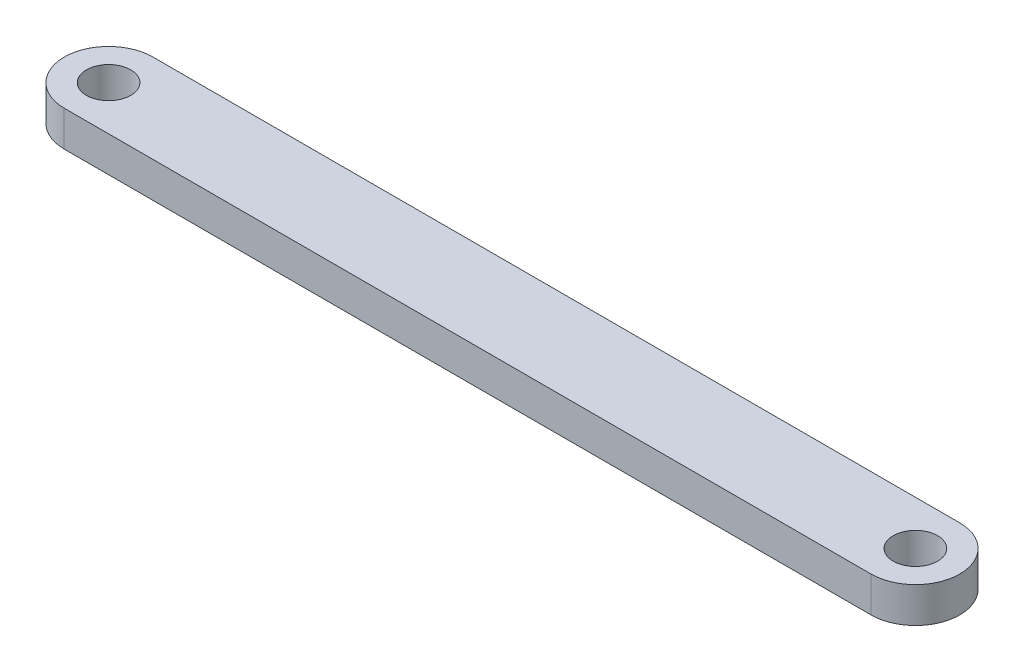
SolidWorks part; units mm, degrees
ref_plane "Alzado" through (0, 0, 0) normal (0, 0, 1) x (1, 0, 0)
ref_plane "Planta" through (0, 0, 0) normal (0, 1, 0) x (1, 0, 0)
ref_plane "Vista lateral" through (0, 0, 0) normal (1, 0, 0) x (0, 0, -1)
sketch "Croquis1" plane through (0, 0, 0) normal (0, 1, 0) x (1, 0, 0)
  line L0 (0, 0) -> (455, 0) construction
  line L1 (0, 25) -> (455, 25)
  line L2 (455, -25) -> (0, -25)
  circle A0 centre (0, 0) radius 25
  circle A1 centre (455, 0) radius 25
  circle A2 centre (0, 0) radius 12.5
  circle A3 centre (455, 0) radius 12.5
  point P12 (450.1575, 0)
  dimension "D2" = 50
  dimension "D3" = 25
  dimension "D1" = 455
extrude "Saliente-Extruir1" add sketch "Croquis1" along normal blind 20
